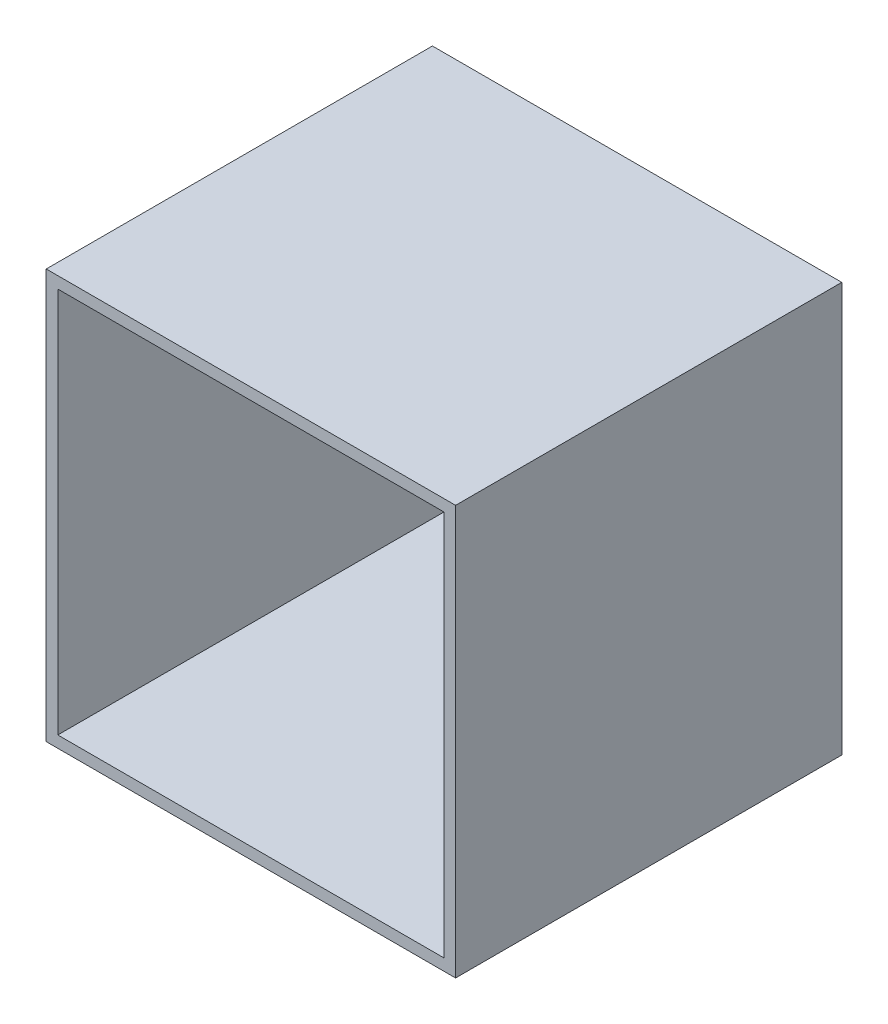
SolidWorks part; units mm, degrees
ref_plane "Alzado" through (0, 0, 0) normal (0, 0, 1) x (1, 0, 0)
ref_plane "Planta" through (0, 0, 0) normal (0, 1, 0) x (1, 0, 0)
ref_plane "Vista lateral" through (0, 0, 0) normal (1, 0, 0) x (0, 0, -1)
sketch "Croquis1" plane through (0, 0, 0) normal (0, 0, 1) x (1, 0, 0)
  line L0 (-3.0879, -5.8025) -> (-3.0879, -105.8025)
  line L1 (-3.0879, -5.8025) -> (96.9121, -5.8025)
  line L2 (-3.0879, -105.8025) -> (96.9121, -105.8025)
  line L3 (96.9121, -5.8025) -> (96.9121, -105.8025)
  line L5 (-6.0879, -2.8025) -> (-6.0879, -108.8025)
  line L6 (-6.0879, -108.8025) -> (99.9121, -108.8025)
  line L7 (99.9121, -2.8025) -> (99.9121, -108.8025)
  line L8 (-6.0879, -2.8025) -> (99.9121, -2.8025)
  dimension "D1" = 100
  dimension "D2" = 100
  dimension "D3" = 3
extrude "Saliente-Extruir1" add sketch "Croquis1" along normal blind 100
